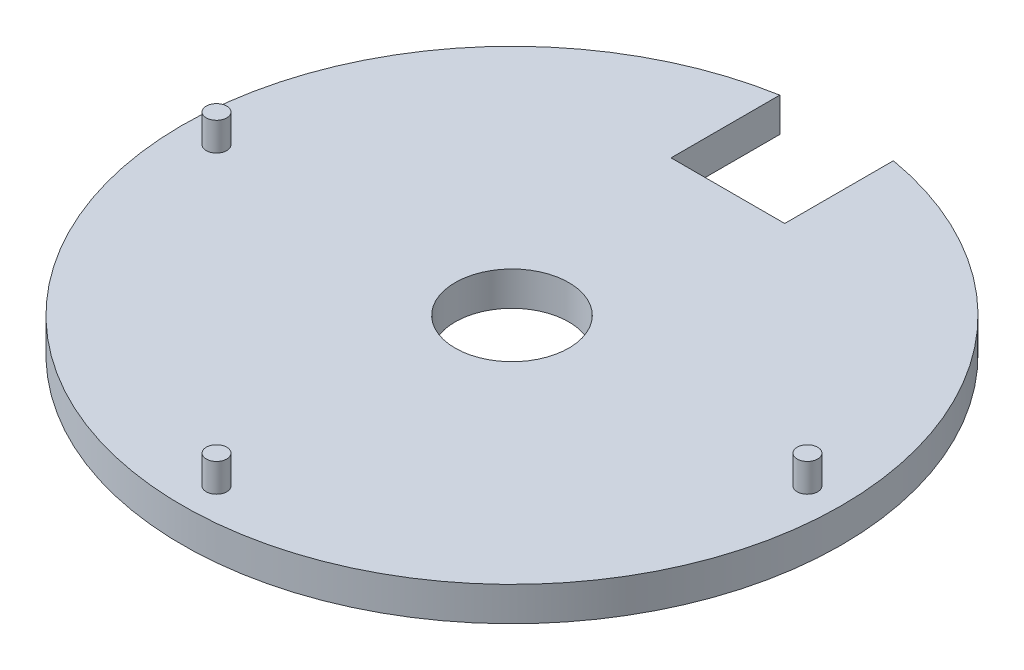
SolidWorks part; units mm, degrees
ref_plane "Front Plane" through (0, 0, 0) normal (0, 0, 1) x (1, 0, 0)
ref_plane "Top Plane" through (0, 0, 0) normal (0, 1, 0) x (1, 0, 0)
ref_plane "Right Plane" through (0, 0, 0) normal (1, 0, 0) x (0, 0, -1)
sketch "Sketch1" plane through (0, 0, 0) normal (0, 1, 0) x (1, 0, 0)
  circle A0 centre (0, 0) radius 29
extrude "Boss-Extrude1" add sketch "Sketch1" along normal blind 3 contours A0
sketch "Sketch6" plane through (0, 3, 0) normal (0, 1, 0) x (1, 0, 0)
  line L0 (0, 0) -> (26, 0)
  line L1 (0, 0) -> (-26, 0)
  line L2 (0, 0) -> (0, -26)
  circle A0 centre (-26, 0) radius 0.9
  circle A1 centre (26, 0) radius 0.9
  circle A2 centre (0, -26) radius 0.9
extrude "Boss-Extrude3" add sketch "Sketch6" along normal blind 2.5 contours A0 | A1
sketch "Sketch7" plane through (0, 3, 0) normal (0, 1, 0) x (1, 0, 0)
  circle A0 centre (0, -26) radius 0.9
extrude "Boss-Extrude4" add sketch "Sketch7" along normal blind 2.5
sketch "Sketch8" plane through (0, 3, 0) normal (0, 1, 0) x (1, 0, 0)
  circle A0 centre (0, 0) radius 5
extrude "Cut-Extrude2" cut sketch "Sketch8" against normal blind 3
sketch "Sketch9" plane through (0, 3, 0) normal (0, 1, 0) x (1, 0, 0)
  line L1 (0, 29) -> (5, 29)
  line L2 (5, 29) -> (5, 19)
  line L3 (5, 19) -> (-5, 19)
  line L4 (-5, 19) -> (-5, 29)
  line L5 (-5, 29) -> (0, 29)
  circle A0 centre (0, 0) radius 29 construction
extrude "Cut-Extrude3" cut sketch "Sketch9" against normal blind 10
